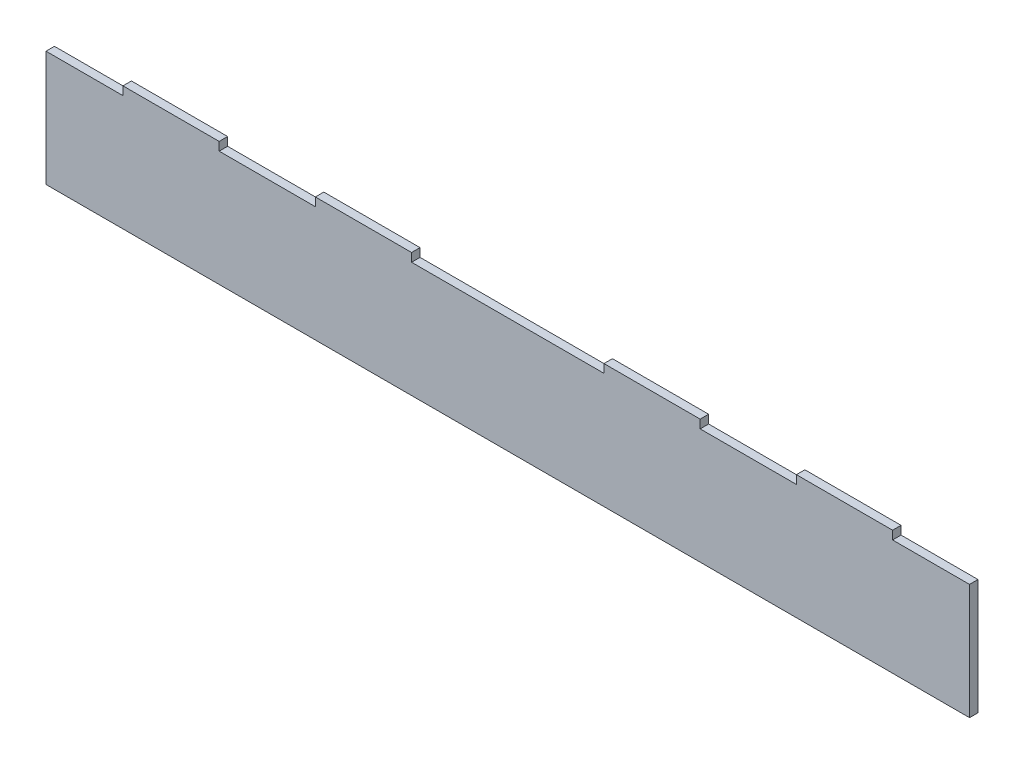
SolidWorks part; units mm, degrees
ref_plane "Front Plane" through (0, 0, 0) normal (0, 0, 1) x (1, 0, 0)
ref_plane "Top Plane" through (0, 0, 0) normal (0, 1, 0) x (1, 0, 0)
ref_plane "Right Plane" through (0, 0, 0) normal (1, 0, 0) x (0, 0, -1)
sketch "Sketch1" plane through (0, 0, 0) normal (0, 0, 1) x (1, 0, 0)
  line L0 (378.4035, -0.118) -> (378.4035, 76.082) construction
  line L1 (73.6035, 76.082) -> (124.4035, 76.082)
  line L2 (73.6035, 76.082) -> (73.6035, -0.118)
  line L3 (73.6035, -0.118) -> (683.2035, -0.118)
  line L4 (683.2035, 76.082) -> (683.2035, -0.118)
  line L5 (441.9035, 81.67) -> (441.9035, 76.082)
  line L6 (124.4035, 76.082) -> (124.4035, 81.67)
  line L7 (124.4035, 81.67) -> (187.9035, 81.67)
  line L8 (187.9035, 76.082) -> (187.9035, 81.67)
  line L9 (251.4035, 81.67) -> (314.9035, 81.67)
  line L10 (251.4035, 81.67) -> (251.4035, 76.082)
  line L11 (505.4035, 81.67) -> (441.9035, 81.67)
  line L12 (314.9035, 81.67) -> (314.9035, 76.082)
  line L13 (187.9035, 76.082) -> (251.4035, 76.082)
  line L14 (314.9035, 76.082) -> (441.9035, 76.082)
  line L15 (505.4035, 81.67) -> (505.4035, 76.082)
  line L16 (568.9035, 76.082) -> (505.4035, 76.082)
  line L17 (568.9035, 76.082) -> (568.9035, 81.67)
  line L18 (632.4035, 81.67) -> (568.9035, 81.67)
  line L19 (632.4035, 76.082) -> (632.4035, 81.67)
  line L20 (683.2035, 76.082) -> (632.4035, 76.082)
  dimension "D1" = 76.2
  dimension "D2" = 609.6
  dimension "D3" = 63.5
  dimension "D4" = 63.5
  dimension "D5" = 63.5
  dimension "D6" = 5.588
extrude "Boss-Extrude1" add sketch "Sketch1" along normal blind 5.588
equation "\"width\"= 9in"
equation "\"Height\"= 18in"
equation "\"thick\"= 0.22"
equation "\"D6@Sketch1\"=\"thick\""
equation "\"D1@Boss-Extrude1\"=\"thick\""
